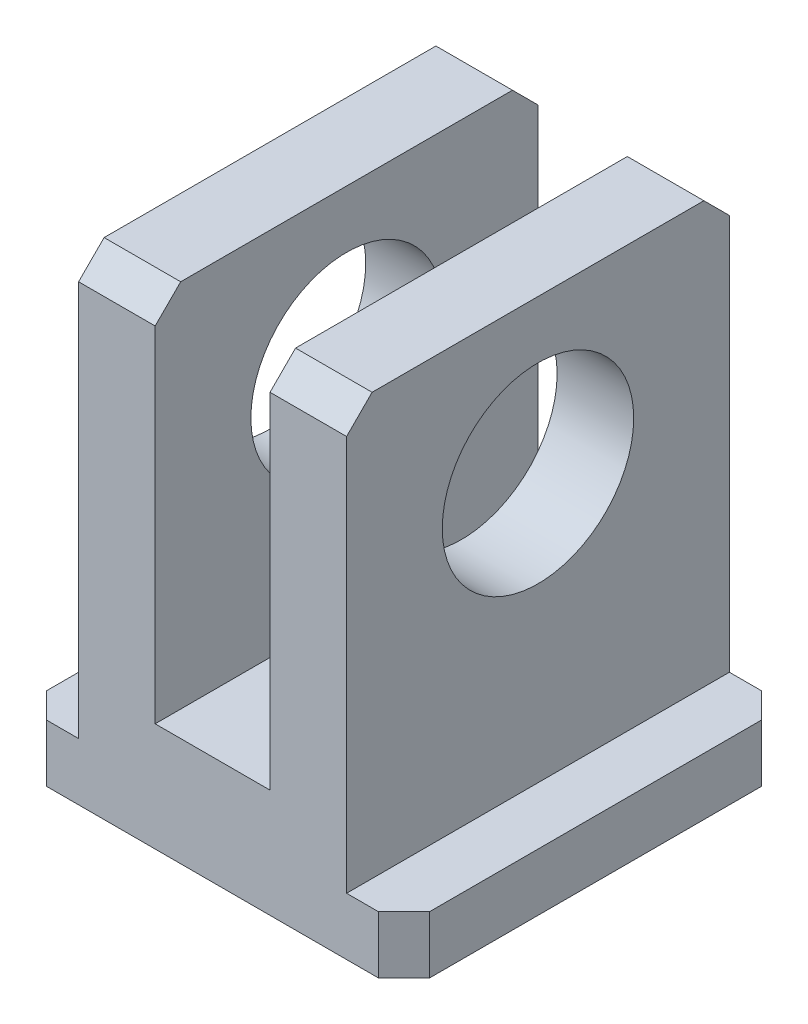
SolidWorks part; units mm, degrees
ref_plane "前视基准面" through (0, 0, 0) normal (0, 0, 1) x (1, 0, 0)
ref_plane "上视基准面" through (0, 0, 0) normal (0, 1, 0) x (1, 0, 0)
ref_plane "右视基准面" through (0, 0, 0) normal (1, 0, 0) x (0, 0, -1)
other "Configuration Table"
sketch "草图1" plane through (0, 0, 0) normal (0, 1, 0) x (1, 0, 0)
  line L0 (-15, 13) -> (-13, 15)
  line L1 (-13, -15) -> (13, -15)
  line L2 (-15, -13) -> (-15, 13)
  line L3 (-13, 15) -> (13, 15)
  line L4 (15, -13) -> (15, 13)
  line L5 (-15, -15) -> (15, 15) construction
  line L6 (-15, 15) -> (15, -15) construction
  line L7 (13, 15) -> (15, 13)
  line L8 (13, -15) -> (15, -13)
  line L9 (-15, -13) -> (-13, -15)
  point P0 (0, 0)
  dimension "D1" = 30
  dimension "D2" = 30
extrude "凸台-拉伸1" add sketch "草图1" along normal blind 37.5
sketch "草图2" plane through (0, 37.5, 0) normal (0, 1, 0) x (1, 0, 0)
  line L0 (-10.5, 15) -> (-10.5, -15)
  line L1 (13, 15) -> (-13, 15) construction
  line L2 (-13, -15) -> (13, -15) construction
  line L3 (0, 15) -> (0, -15) construction
  line L4 (-15, 13) -> (-15, -13) construction
  line L5 (10.5, 15) -> (10.5, -15)
  line L6 (-10.5, 15) -> (-13, 15)
  line L7 (-13, 15) -> (-15, 13)
  line L8 (-15, 13) -> (-15, -13)
  line L9 (-15, -13) -> (-13, -15)
  line L10 (-13, -15) -> (-10.5, -15)
  line L11 (15, -13) -> (13, -15)
  line L12 (15, 13) -> (15, -13)
  line L13 (13, 15) -> (15, 13)
  line L14 (10.5, 15) -> (13, 15)
  line L15 (10.5, 15) -> (10.5, -15)
  line L16 (13, -15) -> (10.5, -15)
  dimension "D1" = 4.5
extrude "切除-拉伸1" cut sketch "草图2" against normal blind 33 contours L10 L0 L6 L7 L8 L9
sketch "草图5" plane through (0, 37.5, 0) normal (0, 1, 0) x (1, 0, 0)
  line L0 (10.5, 15) -> (10.5, -15)
  line L1 (13, 15) -> (-10.5, 15) construction
  line L2 (-10.5, -15) -> (13, -15) construction
  line L3 (15, -13) -> (15, 13) construction
  line L4 (10.5, 15) -> (13, 15)
  line L5 (13, 15) -> (15, 13)
  line L6 (15, 13) -> (15, -13)
  line L7 (15, -13) -> (13, -15)
  line L8 (13, -15) -> (15, -13) construction
  line L9 (13, -15) -> (10.5, -15)
  dimension "D1" = 4.5
extrude "切除-拉伸2" cut sketch "草图5" against normal blind 33
sketch "草图6" plane through (0, 37.5, 0) normal (0, 1, 0) x (1, 0, 0)
  line L0 (0, 15) -> (4.5, 15)
  line L1 (10.5, 15) -> (-10.5, 15) construction
  line L2 (0, 15) -> (-4.5, 15)
  line L3 (-4.5, 15) -> (4.5, 15)
  line L4 (-4.5, 15) -> (-4.5, -15)
  line L5 (-10.5, -15) -> (10.5, -15) construction
  line L6 (-4.5, -15) -> (4.5, -15)
  line L7 (4.5, -15) -> (4.5, 15)
  line L8 (-4.5, 15) -> (4.5, 15)
  line L9 (-4.5, 15) -> (4.5, 15)
  line L10 (-4.5, 15) -> (4.5, 15)
  line M6 (-10.5, -15) -> (10.5, -15)
  line M8 (10.5, 15) -> (-10.5, 15)
extrude "切除-拉伸3" cut sketch "草图6" against normal blind 29 contours L7 L4 M6 M8
sketch "草图11" plane through (10.5, 0, 0) normal (1, 0, 0) x (0, 0, -1)
sketch "草图12" plane through (10.5, 0, 0) normal (1, 0, 0) x (0, 0, -1)
  line L0 (0, 37.5) -> (0, 0) construction
  line L1 (13, 37.5) -> (-13, 37.5) construction
  line L2 (-13, 0) -> (13, 0) construction
  circle A0 centre (0, 25.5) radius 7.5
  dimension "D1" = 25.5
extrude "切除-拉伸5" cut sketch "草图12" against normal through all
sketch "草图14" plane through (10.5, 0, 0) normal (1, 0, 0) x (0, 0, -1)
  line L0 (-15, 37.5) -> (-13, 37.5)
  line L1 (15, 37.5) -> (-15, 37.5) construction
  line L2 (-15, 37.5) -> (-15, 35.5)
  line L3 (-13, 37.5) -> (-15, 35.5)
extrude "切除-拉伸6" cut sketch "草图14" against normal through all
sketch "草图15" plane through (10.5, 0, 0) normal (1, 0, 0) x (0, 0, -1)
  line L0 (15, 37.5) -> (13, 37.5)
  line L1 (15, 37.5) -> (-13, 37.5) construction
  line L2 (15, 37.5) -> (15, 35.5)
  line L3 (15, 4.5) -> (15, 37.5) construction
  line L4 (13, 37.5) -> (15, 35.5)
extrude "切除-拉伸7" cut sketch "草图15" against normal through all
